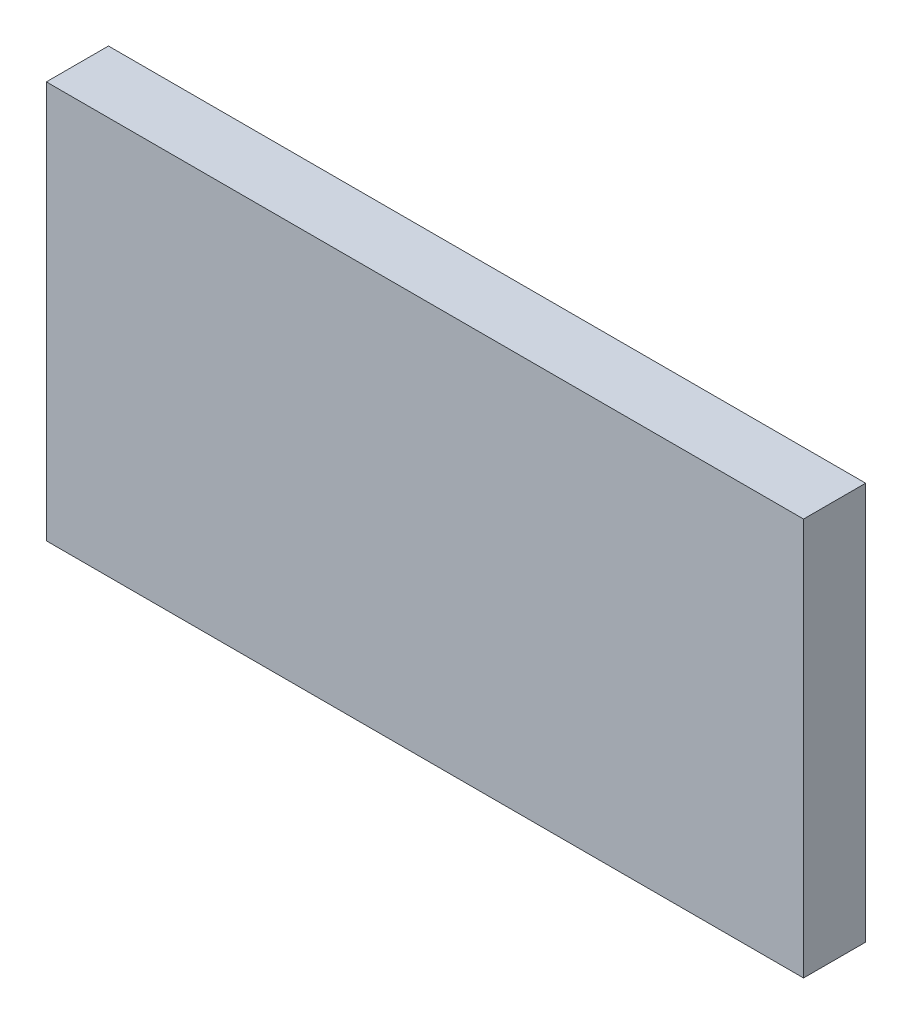
SolidWorks part; units mm, degrees
material "PBT General Purpose"
ref_plane "Front Plane" through (0, 0, 0) normal (0, 0, 1) x (1, 0, 0)
ref_plane "Top Plane" through (0, 0, 0) normal (0, 1, 0) x (1, 0, 0)
ref_plane "Right Plane" through (0, 0, 0) normal (1, 0, 0) x (0, 0, -1)
sketch "Sketch1" plane through (0, 0, 0) normal (0, 0, 1) x (1, 0, 0)
  line L0 (0, 0) -> (0, 32)
  line L1 (0, 32) -> (60.96, 32)
  line L2 (60.96, 32) -> (60.96, 0)
  line L3 (60.96, 0) -> (0, 0)
extrude "Boss-Extrude1" add sketch "Sketch1" against normal blind 5
